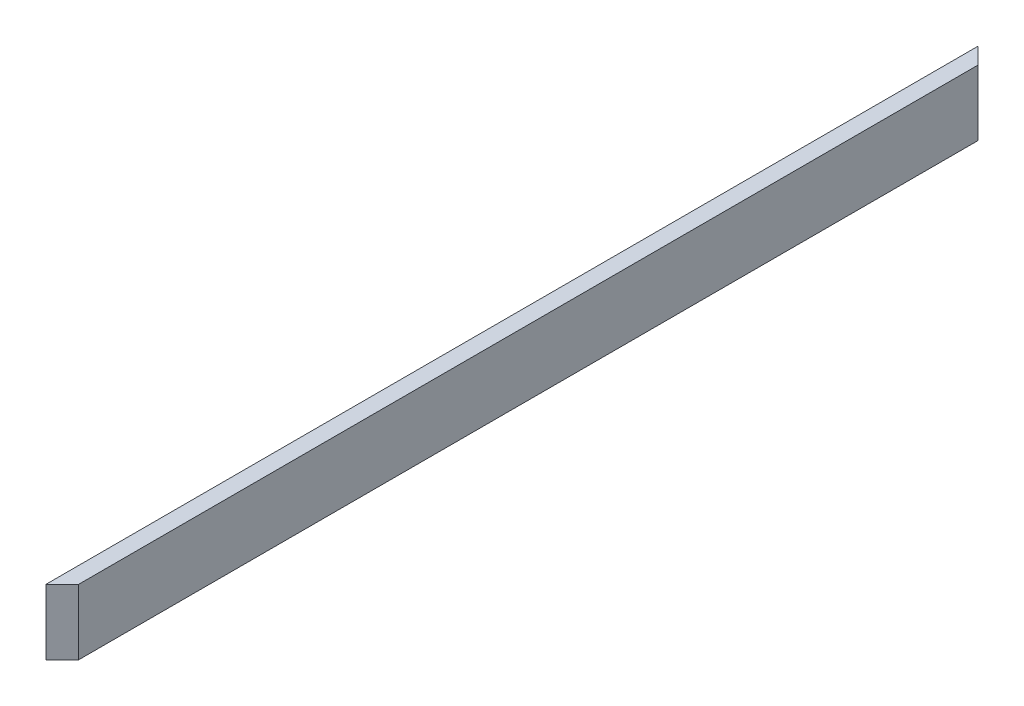
SolidWorks part; units mm, degrees
ref_plane "Plan de face" through (0, 0, 0) normal (0, 0, 1) x (1, 0, 0)
ref_plane "Plan de dessus" through (0, 0, 0) normal (0, 1, 0) x (1, 0, 0)
ref_plane "Plan de droite" through (0, 0, 0) normal (1, 0, 0) x (0, 0, -1)
sketch "Esquisse1" plane through (0, 0, 0) normal (0, 0, 1) x (1, 0, 0)
  line L0 (-10, 40) -> (-10, 0)
  line L3 (-10, 0) -> (0, 0)
  line L4 (0, 0) -> (0, 40)
  line L5 (0, 40) -> (-10, 40)
  point P2 (0, 0)
  point P3 (-6.6247, 0)
  dimension "D3" = 10
  dimension "D4" = 40
extrude "Boss.-Extru.1" add sketch "Esquisse1" along normal mid plane 600
sketch "Esquisse2" plane through (0, 0, 0) normal (0, -1, 0) x (1, 0, 0)
  line L0 (0, 275) -> (-10, 285)
  line L3 (-10, 285) -> (-10, 300)
  line L4 (-10, 300) -> (0, 300)
  line L5 (0, 300) -> (0, 275)
  line L6 (0, 300) -> (0, -300) construction
  line L7 (-10, 300) -> (-10, -300) construction
  point P2 (-10, 300)
  point P3 (0, 275)
  point P4 (-10, 285)
  point P6 (0, 275)
  dimension "D1" = 275
  dimension "D2" = 45
extrude "Enlèv. mat.-Extru.1" cut sketch "Esquisse2" against normal through all both and the other way through all
mirror "Symétrie1" about plane through (0, 0, 0) normal (0, 0, 1) of "Enlèv. mat.-Extru.1"
